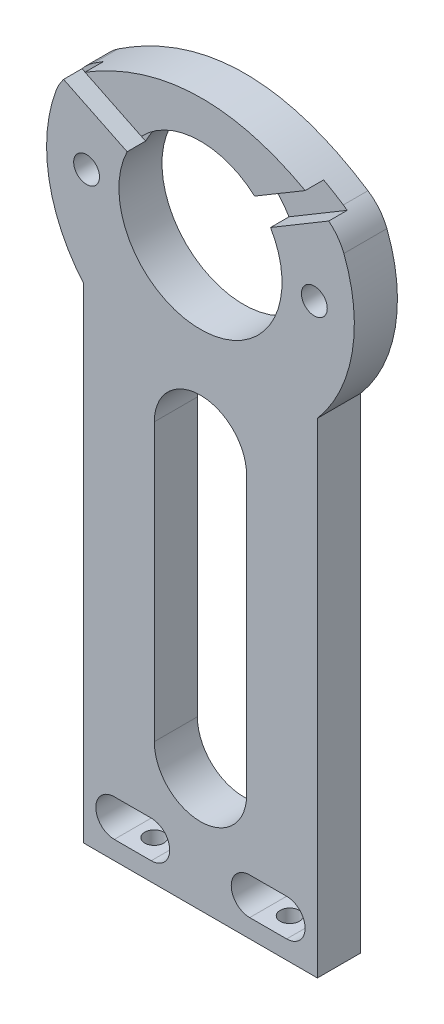
SolidWorks part; units mm, degrees
material "6061 合金"
ref_plane "前视基准面" through (0, 0, 0) normal (0, 0, 1) x (1, 0, 0)
ref_plane "上视基准面" through (0, 0, 0) normal (0, 1, 0) x (1, 0, 0)
ref_plane "右视基准面" through (0, 0, 0) normal (1, 0, 0) x (0, 0, -1)
sketch "草图1" plane through (0, 0, 0) normal (0, 0, 1) x (1, 0, 0)
  line L0 (0, 0) -> (0, 95) construction
  line L1 (-19, 0) -> (19, 0)
  line L2 (-19, 0) -> (-19, 7)
  line L3 (0, 65) -> (0, 20) construction
  line L4 (19, 7) -> (19, 0)
  line L5 (19, 67.2468) -> (19, 7)
  line L6 (-19, 67.2468) -> (-19, 7)
  line L7 (7.5, 65) -> (7.5, 20)
  line L8 (-7.5, 65) -> (-7.5, 20)
  line L9 (-8, 6) -> (-14, 6) construction
  line L10 (-8, 3) -> (-14, 3)
  line L11 (-8, 9) -> (-14, 9)
  line L12 (8, 6) -> (14, 6) construction
  line L13 (8, 3) -> (14, 3)
  line L14 (8, 9) -> (14, 9)
  line L15 (19, 67.2468) -> (19, 79.8153)
  line L16 (-19, 67.2468) -> (-19, 78.7519)
  circle A0 centre (0, 95) radius 13.25
  arc A1 (7.5, 65) -> (-7.5, 65) centre (0, 65) ccw
  arc A2 (19, 67.2468) -> (16.2672, 76.0164) centre (19.5206, 72.2196) cw
  circle A3 centre (0, 95) radius 25
  arc A4 (-7.5, 20) -> (7.5, 20) centre (0, 20) ccw
  arc A5 (-19, 67.2468) -> (-16.2672, 76.0164) centre (-19.5206, 72.2196) ccw
  arc A9 (-8, 3) -> (-8, 9) centre (-8, 6) ccw
  arc A10 (-14, 9) -> (-14, 3) centre (-14, 6) ccw
  arc A11 (8, 3) -> (8, 9) centre (8, 6) cw
  arc A12 (14, 9) -> (14, 3) centre (14, 6) cw
  point P9 (0, 42.5)
  point P30 (0, 95)
  point P31 (-11, 6)
  point P38 (11, 6)
  dimension "D4" = 50
  dimension "D5" = 20
  dimension "D6" = 30
  dimension "D7" = 7.5
  dimension "D2" = 26.5
  dimension "D3" = 95
  dimension "D12" = 5
  dimension "D13" = 3
  dimension "D14" = 6
  dimension "D15" = 8
  dimension "D16" = 6
  dimension "D1" = 38
extrude "凸台-拉伸1" add sketch "草图1" along normal mid plane 7
sketch "Sketch4" plane through (0, 0, 0) normal (0, -1, 0) x (-1, 0, 0)
  line L0 (0, 0) -> (0, -24.1061) construction
  line L1 (-19, 0) -> (19, 0) construction
  line L3 (19, -3.5) -> (19, 3.5) construction
  line L4 (-19, -3.5) -> (-19, 3.5) construction
  circle A0 centre (11, 0) radius 1.55
  circle A1 centre (-11, 0) radius 1.55
  dimension "D1" = 3.1
  dimension "D2" = 8
extrude "Cut-Extrude5" cut sketch "Sketch4" against normal blind 5
sketch "Sketch6" [suppressed] plane through (0, 0, -3.5) normal (0, 0, -1) x (-1, 0, 0)
  line L0 (-19, 57) -> (-19, 0) construction
  line L1 (19, 0) -> (-19, 0)
  line L2 (19, 0) -> (19, 5)
  line L3 (19, 5) -> (-19, 5)
  line L4 (-19, 0) -> (-19, 5)
  line L5 (19, 57) -> (19, 0) construction
  line L6 (16, 5) -> (12, 5)
  line L7 (16, 5) -> (16, 55)
  line L8 (16, 55) -> (12, 55)
  line L9 (12, 5) -> (12, 55)
  line L10 (0, 0) -> (0, 140.1945) construction
  line L11 (-16, 55) -> (-12, 55)
  line L12 (-12, 5) -> (-12, 55)
  line L13 (-16, 5) -> (-12, 5)
  line L14 (-16, 5) -> (-16, 55)
  line M7 (-19, 57) -> (-19, 0)
  line M8 (-19, 0) -> (19, 0)
  line M9 (19, 0) -> (19, 57)
  dimension "D1" = 5
  dimension "D2" = 50
  dimension "D3" = 4
  dimension "D4" = 3
sketch "Sketch8" [suppressed] plane through (0, 0, 3.5) normal (0, 0, 1) x (1, 0, 0)
  line L0 (0, 75) -> (0, 115.5563) construction
  circle A0 centre (0, 75) radius 25
  circle A1 centre (0, 95) radius 2.05
  circle A2 centre (-17.3205, 65) radius 2.05
  circle A3 centre (17.3205, 65) radius 2.05
  circle A4 centre (0, 75) radius 12
  arc A5 (-5.0765, 50.5208) -> (5.0765, 50.5208) centre (0, 45) cw
  arc A6 (-13.7658, 95.8687) -> (-6.0766, 85.3477) centre (-16.0458, 86.1321) cw
  arc A7 (13.7658, 95.8687) -> (6.0766, 85.3477) centre (16.0458, 86.1321) ccw
  arc A8 (24.9557, 76.4872) -> (11.9997, 75.0886) centre (17.6635, 83.33) cw
  arc A9 (11.1899, 52.6441) -> (5.9231, 64.5637) centre (1.6178, 55.5379) ccw
  arc A10 (-11.1899, 52.6441) -> (-5.9231, 64.5637) centre (-1.6178, 55.5379) cw
  arc A11 (-24.9557, 76.4872) -> (-11.9997, 75.0886) centre (-17.6635, 83.33) ccw
  point P41 (0, 75)
  arc M2 (20, 60) -> (-20, 60) centre (0, 75) ccw
  circle M7 centre (-17.3205, 65) radius 2.05
  circle M8 centre (17.3205, 65) radius 2.05
  circle M9 centre (0, 95) radius 2.05
  dimension "D1" = 24
  dimension "D2" = 10
  dimension "D3" = 50
extrude "Boss-Extrude3" [suppressed] add sketch "Sketch8" along normal blind 7 contours A11 A0 A10 A4 M2 M7 | L0 A4 A7 A0 A1 | A9 A0 A8 A4 M2 M8 | A4 L0 A6 M9 M2
extrude "Boss-Extrude4" [suppressed] add sketch "Sketch6" along normal blind 10 contours L9 L3 L7 L8 | L14 L3 L12 L11 | L10 L3 M8 M7 | L10 L1 L3 M9
sketch "Sketch9" [suppressed] plane through (16, 0, 0) normal (1, 0, 0) x (0, 0, -1)
  line L2 (3.5, 55) -> (13.5, 55)
  line L3 (13.5, 55) -> (13.5, 5)
  line L5 (13.5, 5) -> (11.5, 5)
  line L6 (11.5, 5) -> (3.5, 55)
  dimension "D1" = 2
extrude "Cut-Extrude6" [suppressed] cut sketch "Sketch9" against normal through all
sketch "Sketch10" [suppressed] plane through (0, 0, 0) normal (0, -1, 0) x (1, 0, 0)
  line L0 (0, 0) -> (0, -46.2023) construction
  line L1 (-19, 3.5) -> (-19, -13.5) construction
  line L2 (19, -13.5) -> (-19, -13.5) construction
  circle A0 centre (-9, -8.5) radius 1.55
  circle A1 centre (9, -8.5) radius 1.55
  dimension "D1" = 3.1
  dimension "D2" = 10
  dimension "D3" = 5
extrude "Cut-Extrude7" [suppressed] cut sketch "Sketch10" against normal blind 10
fillet "Fillet4" [suppressed] radius 2
fillet "Fillet5" [suppressed] radius 2
fillet "Fillet7" [suppressed] radius 5
sketch "草图2" plane through (0, 0, 3.5) normal (0, 0, 1) x (1, 0, 0)
  line L0 (18.5, 95) -> (-18.5, 95) construction
  line L1 (0, 0) -> (0, 173.8063) construction
  circle A0 centre (-18.5, 95) radius 2.1
  circle A1 centre (18.5, 95) radius 2.1
  circle A2 centre (0, 95) radius 13.25 construction
  circle A3 centre (0, 95) radius 13.25
  arc A4 (19, 78.7519) -> (-19, 78.7519) centre (0, 95) ccw construction
  arc A5 (19, 78.7519) -> (-19, 78.7519) centre (0, 95) ccw
  point P5 (0, 95)
  dimension "D2" = 4.2
  dimension "D3" = 4.2
  dimension "D1" = 37
extrude "切除-拉伸1" cut sketch "草图2" against normal blind 10 contours A0 | A1
sketch "草图3" plane through (0, 0, -3.5) normal (0, 0, 1) x (1, 0, 0)
  circle A0 centre (0, 95) radius 13.25 construction
  circle A1 centre (0, 95) radius 13.25
  circle A2 centre (0, 95) radius 6.5
  dimension "D1" = 13
sketch "草图4" plane through (0, 0, -114.5) normal (0, 0, -1) x (-1, 0, 0)
  line L0 (0, 120) -> (0, 108.5) construction
  line L1 (0, 95) -> (-22.1874, 106.5205)
  line L2 (0, 95) -> (22.3863, 106.129)
  line L4 (-22.1874, 106.5205) -> (0, 122.4468) construction
  line L5 (0, 122.4468) -> (22.3863, 106.129) construction
  arc A0 (10.9451, 102.9028) -> (-10.9451, 102.9028) centre (0, 95) ccw construction
  arc A1 (10.9451, 102.9028) -> (-10.9451, 102.9028) centre (0, 95) ccw
  arc A2 (19, 78.7519) -> (-19, 78.7519) centre (0, 95) ccw construction
  arc A4 (19, 78.7519) -> (-19, 78.7519) centre (0, 95) ccw
  spline S0 degree 1 poles (0, 95) (-22.1874, 106.5205) knots 0 0 1 1
  spline S1 degree 1 poles (0, 95) (-22.1874, 106.5205) knots 0 0 1 1
  spline S2 degree 2 poles (-22.1874, 106.5205) (0, 122.4468) (22.3863, 106.129) knots 0 0 0 1 1 1
  arc M4 (19, 78.7519) -> (-19, 78.7519) centre (0, 95) ccw
extrude "切除-拉伸2" cut sketch "草图4" against normal through all contours S2 M4
fillet "圆角1" radius 8 2 edges at (-22.3863, 106.129, 0) (22.1874, 106.5205, 0)
sketch "草图5" plane through (0, 0, 3.5) normal (0, 0, 1) x (1, 0, 0)
  line L0 (0, 95) -> (-22.2386, 105.8154)
  line L1 (-22.2288, 110.2585) -> (-22.2386, 105.8154)
  line L2 (-22.2288, 110.2585) -> (-0.1929, 99.5417)
  line L3 (0, 95) -> (-0.1929, 99.5417)
  line L4 (20.8553, 112.088) -> (-0.1929, 99.5417)
  line L5 (20.8553, 112.088) -> (21.2417, 107.6616)
  line L6 (0, 95) -> (21.2417, 107.6616)
  circle A1 centre (0, 95) radius 13.25 construction
  circle A2 centre (0, 95) radius 13.25 construction
  arc A3 (-20.3873, 107.522) -> (-23.4677, 103.6178) centre (-15.958, 100.8601) ccw construction
  arc M6 (23.2922, 104.0815) -> (20.2121, 107.8742) centre (15.8387, 101.1754) ccw
  spline M7 degree 2 poles (22.1874, 106.5205) (0, 122.4468) (-22.3863, 106.129) knots 0 0 0 1 1 1 only from (20.2121, 107.8742) to (-20.3873, 107.522)
  arc M8 (-20.3873, 107.522) -> (-23.4677, 103.6178) centre (-15.958, 100.8601) ccw
  circle M15 centre (0, 95) radius 13.25
  dimension "D3" = 4
extrude "切除-拉伸3" cut sketch "草图5" against normal blind 3 contours L2 L0 M7 M8 M15 | L6 L4 M15 M6 M7
